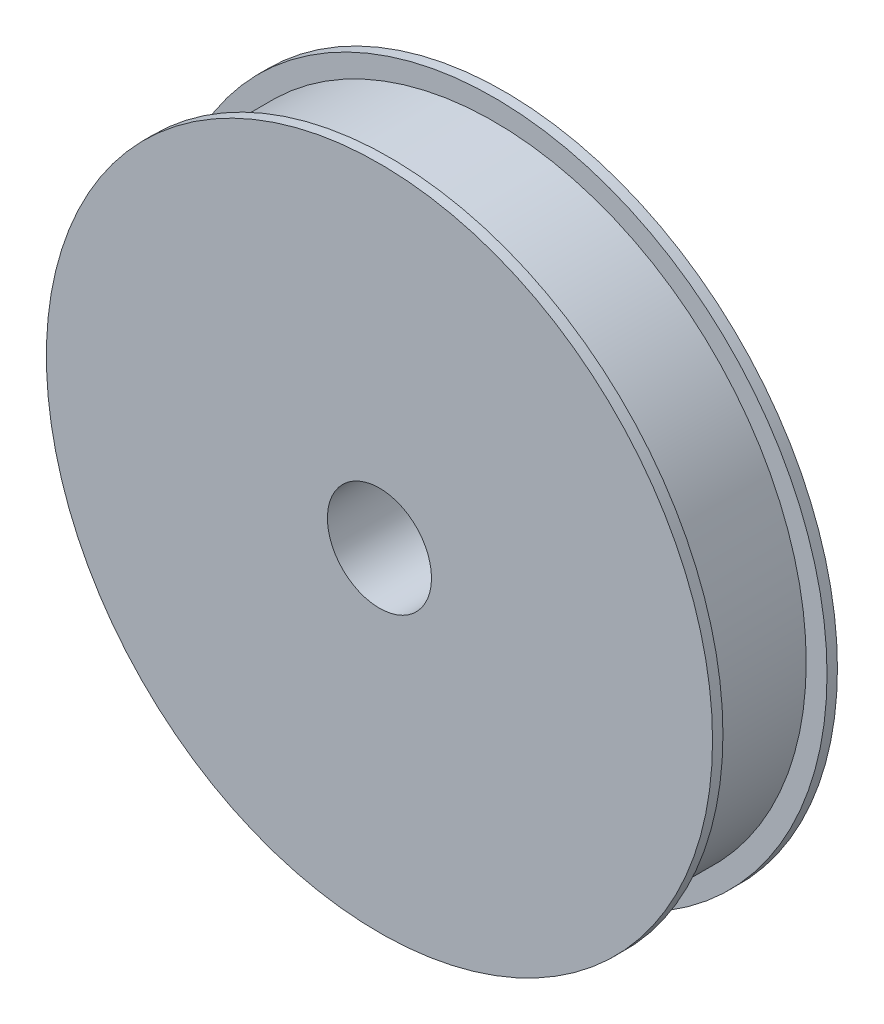
SolidWorks part; units mm, degrees
ref_plane "Front Plane" through (0, 0, 0) normal (0, 0, 1) x (1, 0, 0)
ref_plane "Top Plane" through (0, 0, 0) normal (0, 1, 0) x (1, 0, 0)
ref_plane "Right Plane" through (0, 0, 0) normal (1, 0, 0) x (0, 0, -1)
sketch "Sketch1" plane through (0, 0, 0) normal (1, 0, 0) x (0, 0, -1)
  line L0 (-5, 32) -> (-5, 30)
  line L1 (-6, 32) -> (-5, 32)
  line L2 (-6, 32) -> (-6, 0)
  line L3 (-6, 0) -> (6, 0)
  line L4 (6, 32) -> (6, 0)
  line L9 (-5, 30) -> (5, 30)
  line L10 (5, 30) -> (5, 32)
  line L11 (5, 32) -> (6, 32)
  line L13 (0, 55) -> (0, -55) construction
  point P6 (0, 0)
  dimension "2" = 2
  dimension "D2" = 30
  dimension "D3" = 10
  dimension "D4" = 1
revolve "Revolve1" add sketch "Sketch1" angle 360 about L3
sketch "Sketch3" plane through (0, 0, 0) normal (0, 0, 1) x (1, 0, 0)
  circle A0 centre (0, 0) radius 5
  dimension "D1" = 10
extrude "Cut-Extrude1" cut sketch "Sketch3" against normal through all both and the other way through all
